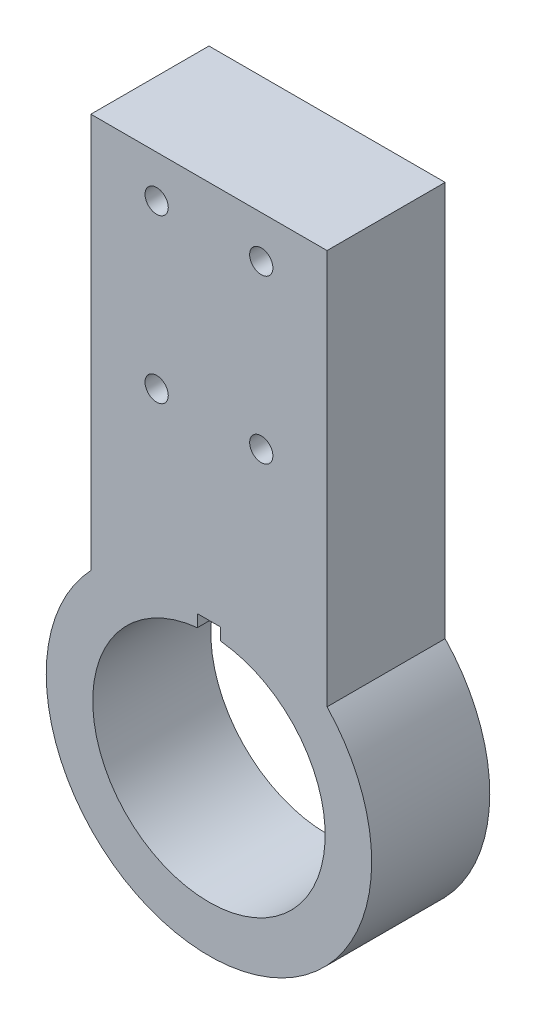
SolidWorks part; units mm, degrees
ref_plane "Front Plane" through (0, 0, 0) normal (0, 0, 1) x (1, 0, 0)
ref_plane "Top Plane" through (0, 0, 0) normal (0, 1, 0) x (1, 0, 0)
ref_plane "Right Plane" through (0, 0, 0) normal (1, 0, 0) x (0, 0, -1)
sketch "Sketch1" plane through (0, 0, 0) normal (0, 0, 1) x (1, 0, 0)
  line L2 (-25.4, 24.0799) -> (-25.4, 109.0799)
  line L3 (-25.4, 109.0799) -> (25.4, 109.0799)
  line L4 (25.4, 24.0799) -> (25.4, 109.0799)
  arc A1 (-25.4, 24.0799) -> (25.4, 24.0799) centre (0, 0) ccw
  circle A2 centre (0, 0) radius 25
  dimension "D5" = 35
  dimension "D2" = 50
  dimension "D1" = 50.8
  dimension "D6" = 85
extrude "Boss-Extrude1" add sketch "Sketch1" along normal blind 25.4
sketch "Sketch2" plane through (0, 0, 25.4) normal (0, 0, 1) x (1, 0, 0)
  line L0 (0, 0) -> (0, 27.5) construction
  line L1 (-2.5, 27.5) -> (2.5, 27.5)
  line L2 (2.5, 27.5) -> (2.5, 0)
  line L3 (2.5, 0) -> (-2.5, 0)
  line L4 (-2.5, 0) -> (-2.5, 27.5)
  point P8 (0, 27.5)
  dimension "D1" = 27.5
  dimension "D2" = 5
extrude "Cut-Extrude1" cut sketch "Sketch2" against normal through all
sketch "Sketch3" plane through (0, 0, 25.4) normal (0, 0, 1) x (1, 0, 0)
  line L0 (-11.25, 100) -> (-25.4, 100) construction
  line L1 (-11.25, 100) -> (11.25, 100) construction
  line L2 (-11.25, 100) -> (-11.25, 65) construction
  line L3 (-11.25, 65) -> (11.25, 65) construction
  line L4 (11.25, 100) -> (11.25, 65) construction
  line L5 (-25.4, 109.0799) -> (-25.4, 24.0799) construction
  line L6 (0, 65) -> (0, 0) construction
  circle A0 centre (-11.25, 100) radius 2.5
  circle A1 centre (11.25, 100) radius 2.5
  circle A2 centre (11.25, 65) radius 2.5
  circle A3 centre (-11.25, 65) radius 2.5
  point P5 (0, 65)
  dimension "D2" = 5
  dimension "D1" = 65
  dimension "D3" = 35
  dimension "D4" = 22.5
extrude "Cut-Extrude2" cut sketch "Sketch3" against normal through all
equation "\"tube_width\"= 1in"
equation "\"tube_height\"= 2in"
equation "\"tube_thickness\"= 0.125in"
equation "\"D1@Sketch1\"=\"tube_height\""
equation "\"D1@Boss-Extrude1\"=\"tube_width\""
